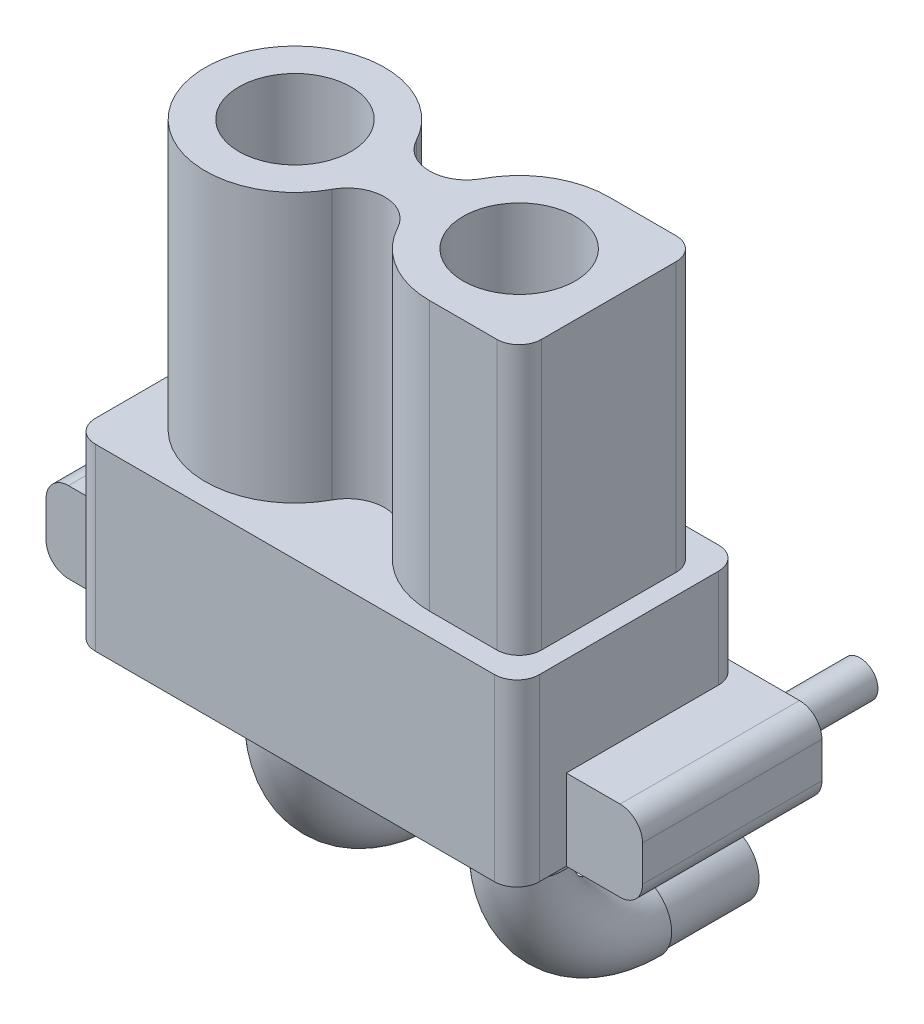
SolidWorks part; units mm, degrees
material "5052-H38"
ref_plane "Front" through (0, 0, 0) normal (0, 0, 1) x (1, 0, 0)
ref_plane "Top" through (0, 0, 0) normal (0, 1, 0) x (1, 0, 0)
ref_plane "Right" through (0, 0, 0) normal (1, 0, 0) x (0, 0, -1)
sketch "ｽｹｯﾁ1" plane through (0, 0, 0) normal (0, 0, 1) x (1, 0, 0)
  circle A0 centre (0, 0) radius 0.75
  dimension "D1" = 1.5
extrude "ﾎﾞｽ - 押し出し1" add sketch "ｽｹｯﾁ1" against normal blind 2
sketch "ｽｹｯﾁ2" plane through (0, 0, 0) normal (0, 0, 1) x (1, 0, 0)
  circle A0 centre (0, 0) radius 0.8
  dimension "D1" = 1.6
sketch "ｽｹｯﾁ3" plane through (0, 0, 0) normal (1, 0, 0) x (0, 0, -1)
  line L0 (-2.6, 2.6) -> (0, 2.6) construction
  line L1 (0, 2.6) -> (0, 0) construction
  arc A0 (0, 0) -> (-2.6, 2.6) centre (0, 2.6) cw
  dimension "D1" = 2.6
sweep "ｽｲｰﾌﾟ1" add profiles "ｽｹｯﾁ2" path "ｽｹｯﾁ3"
sketch "ｽｹｯﾁ4" plane through (0, 2.6, 0) normal (0, 1, 0) x (1, 0, 0)
  circle A0 centre (0, -2.6) radius 1
  circle A1 centre (0, -2.6) radius 0.8 construction
  dimension "D1" = 2
extrude "ﾎﾞｽ - 押し出し2" add sketch "ｽｹｯﾁ4" along normal blind 1.5
sketch "ｽｹｯﾁ5" plane through (0, 4.1, 0) normal (0, 1, 0) x (1, 0, 0)
  line L0 (-2.45, -0.1) -> (-2.45, -5.1)
  line L1 (-2.45, -5.1) -> (7.45, -5.1)
  line L2 (7.45, -5.1) -> (7.45, -0.1)
  line L3 (7.45, -0.1) -> (-2.45, -0.1)
  line L4 (0, -2.6) -> (-2.45, -2.6) construction
  line L5 (0, -2.6) -> (2.5, -2.6) construction
  line L6 (2.5, -2.6) -> (2.5, -0.1) construction
  dimension "D1" = 5
  dimension "D2" = 9.9
  dimension "D3" = 2.5
extrude "ﾎﾞｽ - 押し出し3" add sketch "ｽｹｯﾁ5" along normal blind 4
sketch "ｽｹｯﾁ8" plane through (0, 0, 0) normal (0, 0, 1) x (1, 0, 0)
  line L0 (0, 0) -> (0, 5) construction
  line L1 (0, 5) -> (-3, 5) construction
  line L2 (0, 5) -> (8, 5) construction
  circle A0 centre (-3, 5) radius 0.4
  circle A1 centre (8, 5) radius 0.4
  dimension "D4" = 0.8
  dimension "D1" = 5
  dimension "D2" = 3
  dimension "D3" = 8
extrude "ﾎﾞｽ - 押し出し5" add sketch "ｽｹｯﾁ8" against normal blind 2 separate body
sketch "ｽｹｯﾁ9" plane through (0, 0, 0) normal (0, 0, 1) x (1, 0, 0)
  line L0 (-4.15, 5.9) -> (-4.15, 4.1)
  line L1 (-4.15, 4.1) -> (-1.45, 4.1)
  line L2 (-1.45, 4.1) -> (-1.45, 5.9)
  line L3 (-1.45, 5.9) -> (-4.15, 5.9)
  line L4 (-3, 5) -> (-4.15, 5) construction
  line L5 (7.45, 4.1) -> (-2.45, 4.1) construction
  line L6 (-2.45, 8.1) -> (-2.45, 4.1) construction
  line L7 (6.45, 5.9) -> (6.45, 4.1)
  line L8 (6.45, 4.1) -> (9.15, 4.1)
  line L9 (9.15, 4.1) -> (9.15, 5.9)
  line L10 (9.15, 5.9) -> (6.45, 5.9)
  line L11 (8, 5) -> (9.15, 5) construction
  dimension "D1" = 4.15
  dimension "D2" = 1
extrude "ﾎﾞｽ - 押し出し6" add sketch "ｽｹｯﾁ9" along normal blind 4
sketch "ｽｹｯﾁ6" plane through (0, 8.1, 0) normal (0, 1, 0) x (1, 0, 0)
  line L0 (0, 0) -> (0, -2.6) construction
  line L1 (0.8, 0) -> (-0.8, 0) construction
  line L2 (0, -2.6) -> (-2.45, -2.6) construction
  line L3 (-2.45, -0.1) -> (-2.45, -5.1) construction
  line L4 (0, -0.6) -> (7, -0.6)
  line L5 (7, -0.6) -> (7, -4.6)
  line L6 (7, -4.6) -> (0, -4.6)
  arc A0 (0, -4.6) -> (0, -0.6) centre (0, -2.6) cw
  dimension "D1" = 2
  dimension "D2" = 7
extrude "ﾎﾞｽ - 押し出し4" add sketch "ｽｹｯﾁ6" along normal blind 6
sketch "ｽｹｯﾁ7" plane through (0, 14.1, 0) normal (0, 1, 0) x (1, 0, 0)
  circle A0 centre (0, -2.6) radius 1.25
  arc A1 (0, -0.6) -> (0, -4.6) centre (0, -2.6) ccw construction
  dimension "D1" = 2.5
extrude "ｶｯﾄ - 押し出し1" cut sketch "ｽｹｯﾁ7" against normal blind 6
pattern_linear "直線ﾊﾟﾀｰﾝ1" count 2 spacing 5 along (1, 0, 0) of "ﾎﾞｽ - 押し出し1", "ｽｲｰﾌﾟ1", "ﾎﾞｽ - 押し出し2", "ｶｯﾄ - 押し出し1"
ref_plane "平面1" through (0, 0, 2.6) normal (0, 0, 1) x (1, 0, 0)
sketch "ｽｹｯﾁ10" plane through (0, 14.1, 0) normal (0, 1, 0) x (1, 0, 0)
  line L0 (7, -0.6) -> (0, -0.6) construction
  line L1 (1.7647, -1.6588) -> (3.2353, -1.6588) construction
  line L2 (2.5, -2.1) -> (2.5, -0.6) construction
  line L3 (7, -0.6) -> (0, -0.6) construction
  line L4 (0, -0.6) -> (5, -0.6)
  arc A0 (0, -0.6) -> (1.7647, -1.6588) centre (0, -2.6) cw
  arc A1 (5, -0.6) -> (3.2353, -1.6588) centre (5, -2.6) ccw
  arc A2 (1.7647, -1.6588) -> (3.2353, -1.6588) centre (2.5, -1.2667) ccw
  dimension "D1" = 1.5
extrude "ｶｯﾄ - 押し出し2" cut sketch "ｽｹｯﾁ10" against normal up to surface (6 mm away) up to face at (3, 8.1, 2.6)
mirror "ﾐﾗｰ1" about plane through (0, 0, 2.6) normal (0, 0, 1) of "ｶｯﾄ - 押し出し2"
fillet "ﾌｨﾚｯﾄ1" radius 0.5 4 edges at (-4.15, 5.9, 2) (-4.15, 4.1, 2) (9.15, 4.1, 2) (9.15, 5.9, 2)
fillet "ﾌｨﾚｯﾄ2" radius 0.5 4 edges at (7.45, 7, 0.1) (-2.45, 7, 0.1) (-2.45, 6.1, 5.1) (7.45, 6.1, 5.1)
fillet "ﾌｨﾚｯﾄ3" radius 0.5 2 edges at (7, 11.1, 0.6) (7, 11.1, 4.6)
